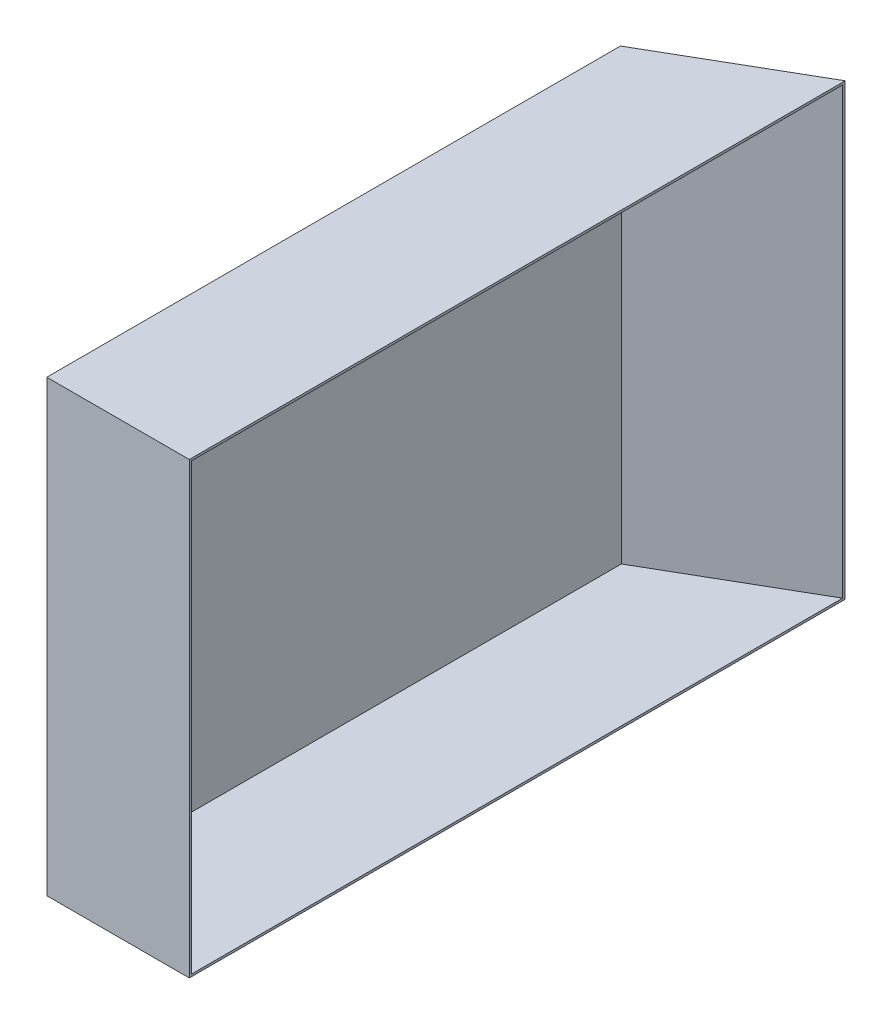
SolidWorks part; units mm, degrees
ref_plane "Front Plane" through (0, 0, 0) normal (0, 0, 1) x (1, 0, 0)
ref_plane "Top Plane" through (0, 0, 0) normal (0, 1, 0) x (1, 0, 0)
ref_plane "Right Plane" through (0, 0, 0) normal (1, 0, 0) x (0, 0, -1)
sketch "Sketch1" plane through (0, 254, 0) normal (0, 1, 0) x (1, 0, 0)
  line L0 (38.1, 150.4353) -> (38.1, 146.5728) construction
  line L1 (196.7763, 227.0317) -> (38.1, 135.4199)
  line L2 (196.7763, 227.0317) -> (196.7763, -503.3093)
  line L3 (196.7763, -503.3093) -> (38.1, -503.3093)
  line L4 (38.1, 135.4199) -> (38.1, -503.3093)
  circle A0 centre (-101.6, -444.5) radius 151.5738 construction
  point P6 (230.1502, 133.0939)
  point P7 (38.1, 63.3822)
  point P10 (197.4284, 194.2695)
  point P11 (38.1, 113.1763)
  point P12 (196.7763, 227.0317)
  dimension "D1" = 120
extrude "Boss-Extrude1" add sketch "Sketch1" against normal blind 500
shell "Shell1" thickness 2.54
